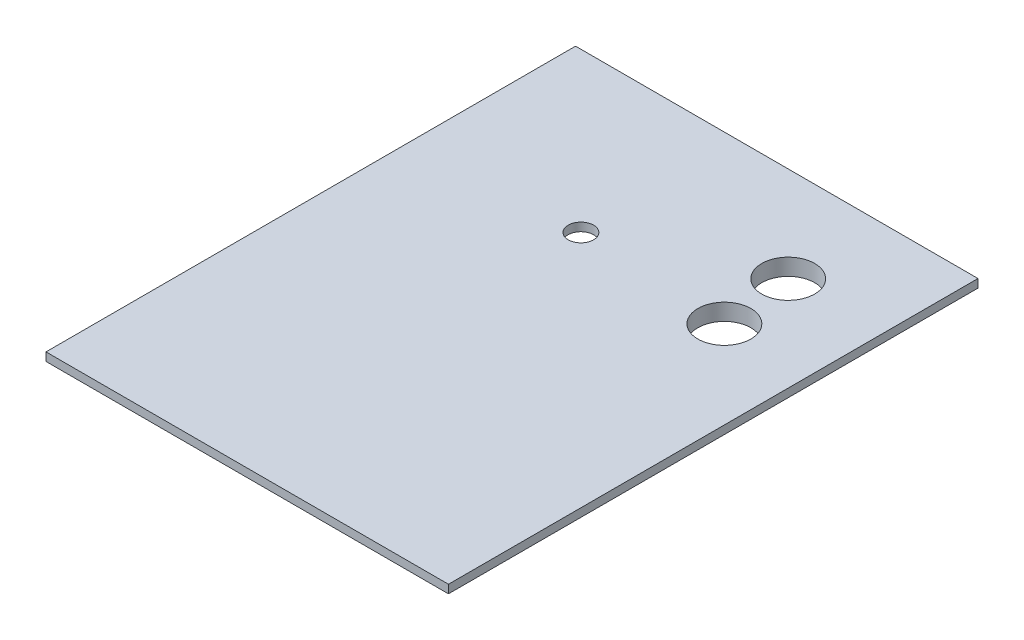
SolidWorks part; units mm, degrees
ref_plane "Front Plane" through (0, 0, 0) normal (0, 0, 1) x (1, 0, 0)
ref_plane "Top Plane" through (0, 0, 0) normal (0, 1, 0) x (1, 0, 0)
ref_plane "Right Plane" through (0, 0, 0) normal (1, 0, 0) x (0, 0, -1)
sketch "Sketch1" plane through (0, -11.3426, 0) normal (0, 1, 0) x (1, 0, 0)
  line L1 (0, 0) -> (48.26, 0)
  line L2 (0, 0) -> (0, -63.5)
  line L3 (0, -63.5) -> (48.26, -63.5)
  line L4 (48.26, 0) -> (48.26, -63.5)
extrude "Boss-Extrude1" add sketch "Sketch1" along normal blind 1
sketch "Sketch3" plane through (0, -11.3426, 0) normal (0, -1, 0) x (1, 0, 0)
  circle A0 centre (5.0673, 58.3463) radius 1.143
  circle A2 centre (27.3101, 5.7201) radius 1.143
  dimension "D1" = 2.286
extrude "Boss-Extrude2" add sketch "Sketch3" along normal blind 3
sketch "Sketch4" plane through (0, -11.3426, 0) normal (0, -1, 0) x (1, 0, 0)
  circle A0 centre (5.0673, 58.3463) radius 2.524
  circle A4 centre (5.0673, 58.3463) radius 1.143 construction
  circle A5 centre (5.0673, 58.3463) radius 1.524 construction
  circle A6 centre (37.7546, 19.906) radius 4.064
  circle A7 centre (36.9062, 11.4046) radius 4.064
  circle A8 centre (27.3101, 5.7201) radius 2.524
  dimension "D1" = 1
  dimension "D2" = 8.128
extrude "Boss-Extrude3" add sketch "Sketch4" along normal blind 1
sketch "Sketch2" plane through (0, -11.3426, 0) normal (0, -1, 0) x (1, 0, 0)
  circle A0 centre (37.7546, 19.906) radius 3.175
  circle A1 centre (36.9062, 11.4046) radius 3.175
  circle A3 centre (19.6723, 19.0271) radius 1.524
  dimension "D1" = 3.048
extrude "Cut-Extrude1" cut sketch "Sketch2" against normal through all both and the other way through all
